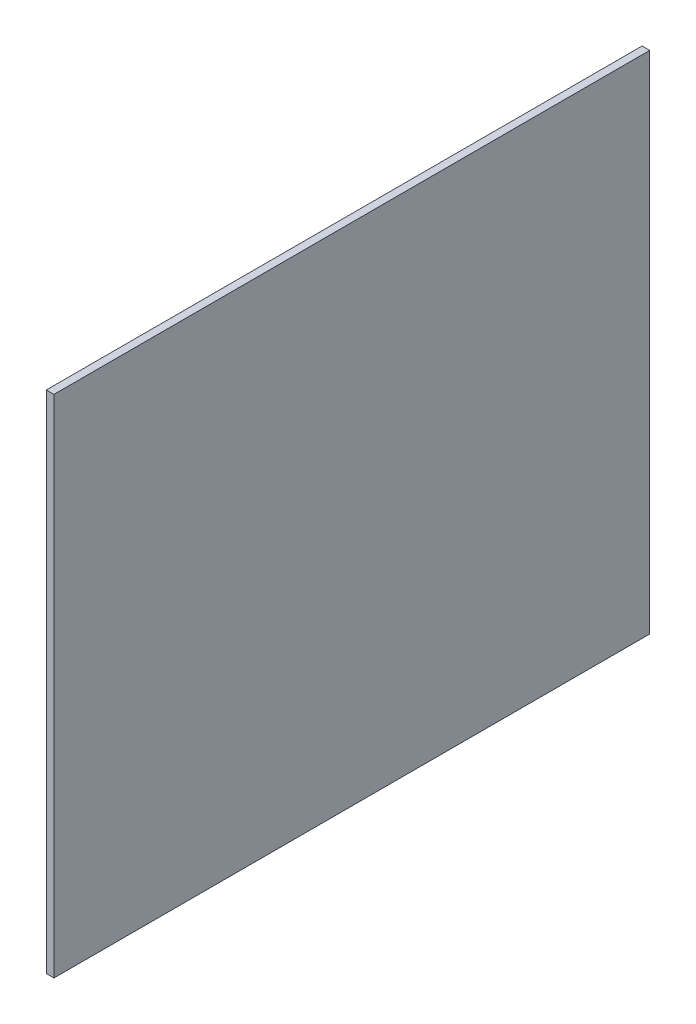
SolidWorks part; units mm, degrees
ref_plane "Front Plane" through (0, 0, 0) normal (0, 0, 1) x (1, 0, 0)
ref_plane "Top Plane" through (0, 0, 0) normal (0, 1, 0) x (1, 0, 0)
ref_plane "Right Plane" through (0, 0, 0) normal (1, 0, 0) x (0, 0, -1)
sketch "Sketch2" plane through (0, 0, 0) normal (1, 0, 0) x (0, 0, -1)
  line L1 (-61.976, -52.578) -> (61.976, -52.578)
  line L2 (-61.976, -52.578) -> (-61.976, 52.578)
  line L3 (-61.976, 52.578) -> (61.976, 52.578)
  line L4 (61.976, -52.578) -> (61.976, 52.578)
  line L5 (-61.976, -52.578) -> (61.976, 52.578) construction
  line L6 (-61.976, 52.578) -> (61.976, -52.578) construction
  point P0 (0, 0)
  dimension "D1" = 105.156
  dimension "D2" = 123.952
extrude "Boss-Extrude1" add sketch "Sketch2" along normal blind 1.5875
